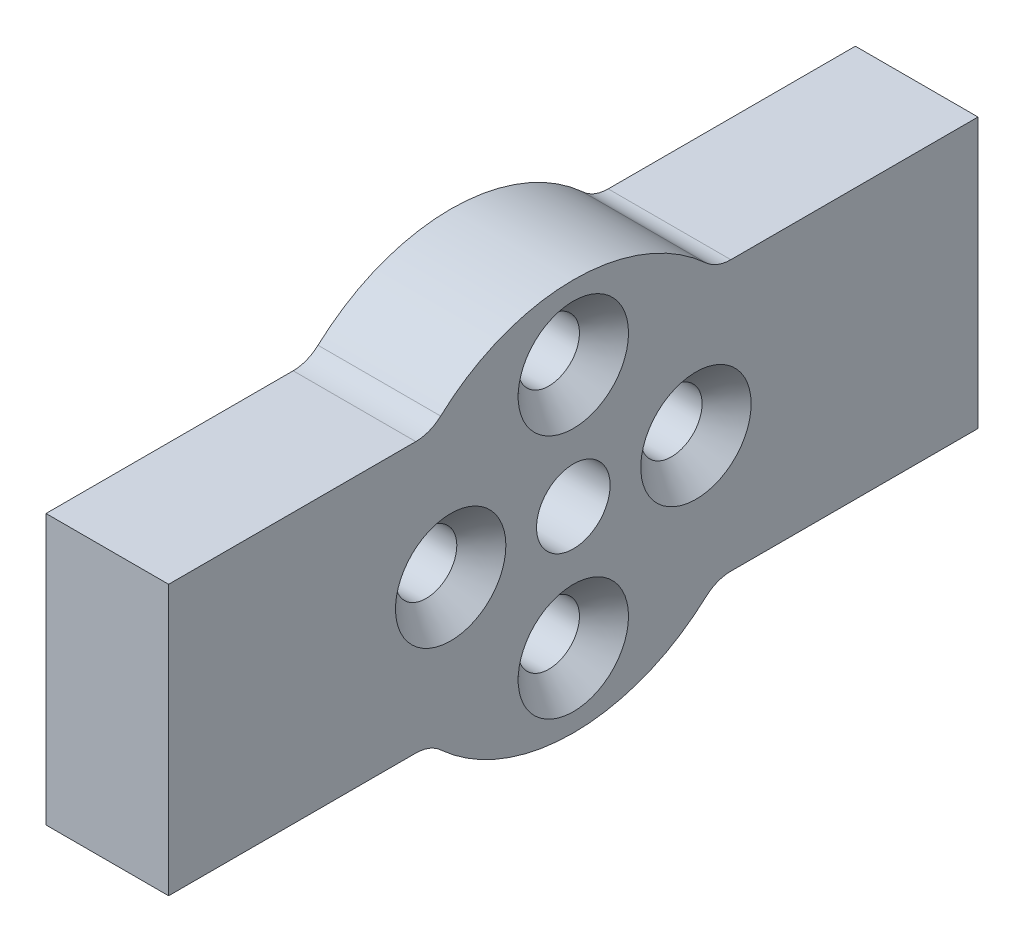
SolidWorks part; units mm, degrees
ref_plane "Спереди" through (0, 0, 0) normal (0, 0, 1) x (1, 0, 0)
ref_plane "Сверху" through (0, 0, 0) normal (0, 1, 0) x (1, 0, 0)
ref_plane "Справа" through (0, 0, 0) normal (1, 0, 0) x (0, 0, -1)
sketch "Эскиз1" plane through (0, 0, 0) normal (1, 0, 0) x (0, 0, -1)
  line L0 (12.8452, 11) -> (33, 11)
  line L1 (-33, 11) -> (-12.8452, 11)
  line L2 (-33, 11) -> (-33, -11)
  line L3 (-33, -11) -> (-12.8452, -11)
  line L4 (33, 11) -> (33, -11)
  line L5 (-33, 11) -> (33, -11) construction
  line L6 (-33, -11) -> (33, 11) construction
  line L7 (12.8452, -11) -> (33, -11)
  arc A0 (-10.817, -11.7895) -> (10.817, -11.7895) centre (0, 0) ccw
  arc A1 (10.817, 11.7895) -> (-10.817, 11.7895) centre (0, 0) ccw
  arc A2 (-10.817, 11.7895) -> (-12.8452, 11) centre (-12.8452, 14) cw
  arc A3 (12.8452, 11) -> (10.817, 11.7895) centre (12.8452, 14) cw
  arc A4 (12.8452, -11) -> (10.817, -11.7895) centre (12.8452, -14) ccw
  arc A5 (-12.8452, -11) -> (-10.817, -11.7895) centre (-12.8452, -14) cw
  point P14 (11.619, 11)
  point P17 (11.619, -11)
  dimension "D1" = 3
  dimension "D2" = 33
extrude "Вытянуть1" add sketch "Эскиз1" along normal blind 10
sketch "Эскиз2" plane through (10, 0, 0) normal (1, 0, 0) x (0, 0, -1)
  circle A0 centre (0, 0) radius 10 construction
  circle A1 centre (0, 10) radius 2.5
  circle A2 centre (10, 0) radius 2.5
  circle A3 centre (0, -10) radius 2.5
  circle A4 centre (-10, 0) radius 2.5
extrude "Вытянуть2" cut sketch "Эскиз2" against normal through all
sketch "Эскиз4" plane through (10, 0, 0) normal (1, 0, 0) x (0, 0, -1)
  circle A0 centre (0, 0) radius 10 construction
  circle A1 centre (0, 10) radius 4.5
  circle A2 centre (10, 0) radius 4.5
  circle A3 centre (0, -10) radius 4.5
  circle A4 centre (-10, 0) radius 4.5
extrude "Вытянуть3" cut sketch "Эскиз4" against normal blind 2 draft 45
sketch "Эскиз5" plane through (10, 0, 0) normal (1, 0, 0) x (0, 0, -1)
  circle A0 centre (0, 0) radius 3
extrude "Вытянуть4" cut sketch "Эскиз5" against normal through all
